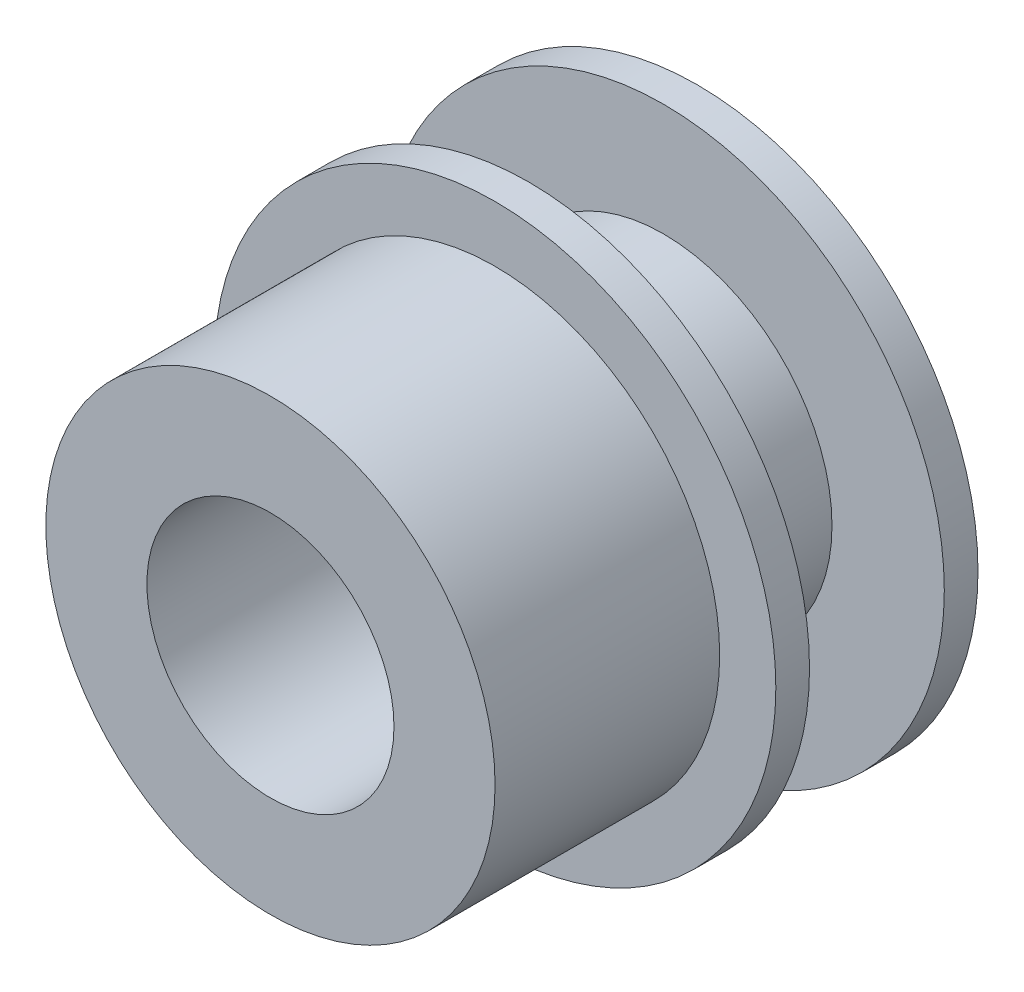
SolidWorks part; units mm, degrees
ref_plane "Front Plane" through (0, 0, 0) normal (0, 0, 1) x (1, 0, 0)
ref_plane "Top Plane" through (0, 0, 0) normal (0, 1, 0) x (1, 0, 0)
ref_plane "Right Plane" through (0, 0, 0) normal (1, 0, 0) x (0, 0, -1)
sketch "Sketch1" plane through (0, 0, 0) normal (0, 0, 1) x (1, 0, 0)
  circle A0 centre (0, 0) radius 25
  dimension "D1" = 50
extrude "Boss-Extrude1" add sketch "Sketch1" along normal blind 3
sketch "Sketch2" plane through (0, 0, 0) normal (0, 0, 1) x (1, 0, 0)
  circle A0 centre (0, 0) radius 15
  dimension "D1" = 30
extrude "Boss-Extrude2" add sketch "Sketch2" along normal blind 15
sketch "Sketch3" plane through (0, 0, 15) normal (0, 0, 1) x (1, 0, 0)
  circle A0 centre (0, 0) radius 25
extrude "Boss-Extrude3" add sketch "Sketch3" along normal blind 3
sketch "Sketch4" plane through (0, 0, 18) normal (0, 0, 1) x (1, 0, 0)
  circle A0 centre (0, 0) radius 20
extrude "Boss-Extrude4" add sketch "Sketch4" along normal blind 20
sketch "Sketch5" plane through (0, 0, 38) normal (0, 0, 1) x (1, 0, 0)
  circle A0 centre (0, 0) radius 11
extrude "Cut-Extrude1" cut sketch "Sketch5" against normal blind 50
